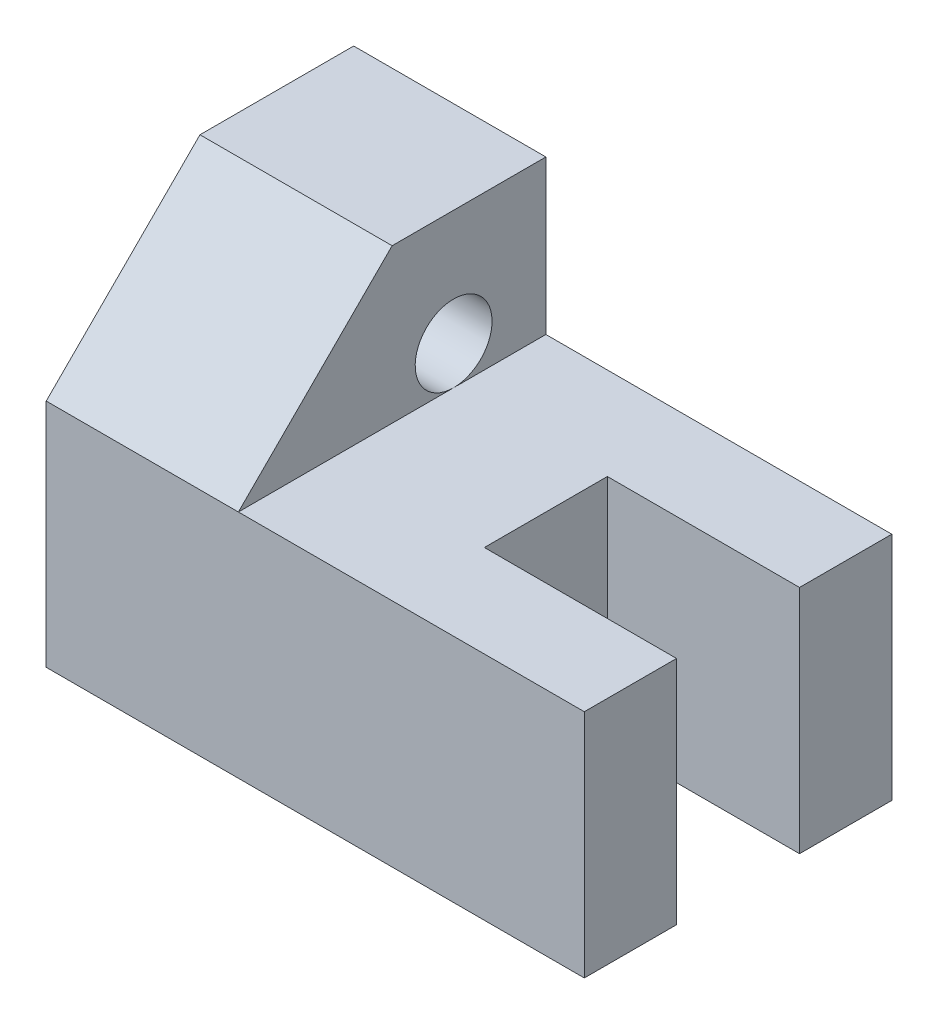
SolidWorks part; units mm, degrees
ref_plane "前视基准面" through (0, 0, 0) normal (0, 0, 1) x (1, 0, 0)
ref_plane "上视基准面" through (0, 0, 0) normal (0, 1, 0) x (1, 0, 0)
ref_plane "右视基准面" through (0, 0, 0) normal (1, 0, 0) x (0, 0, -1)
sketch "草图1" plane through (0, 0, 0) normal (0, 1, 0) x (1, 0, 0)
  line L0 (0, 0) -> (70, 0)
  line L1 (70, 0) -> (70, -40)
  line L2 (70, -40) -> (0, -40)
  line L3 (0, -40) -> (0, 0)
extrude "凸台-拉伸1" add sketch "草图1" along normal blind 30
ref_plane "基准面1" through (0, 30, 0) normal (0, 1, 0) x (1, 0, 0)
sketch "草图6" plane through (0, 30, 0) normal (0, 1, 0) x (1, 0, 0)
  line L0 (45, -12) -> (70, -12)
  line L1 (70, -12) -> (70, -28)
  line L2 (70, -28) -> (45, -28)
  line L3 (45, -28) -> (45, -12)
extrude "切除-拉伸2" cut sketch "草图6" against normal through all
sketch "草图9" plane through (0, 0, 0) normal (1, 0, 0) x (0, 0, -1)
  line L0 (0, 0) -> (-40, 0)
  line L1 (-40, 0) -> (-40, 30)
  line L2 (-40, 30) -> (-20, 50)
  line L3 (-20, 50) -> (0, 50)
  line L4 (0, 50) -> (0, 0)
extrude "凸台-拉伸6" add sketch "草图9" along normal blind 25
sketch "草图10" plane through (0, 0, 0) normal (1, 0, 0) x (0, 0, -1)
  circle A0 centre (-12, 35) radius 5
extrude "切除-拉伸4" cut sketch "草图10" along normal through all
